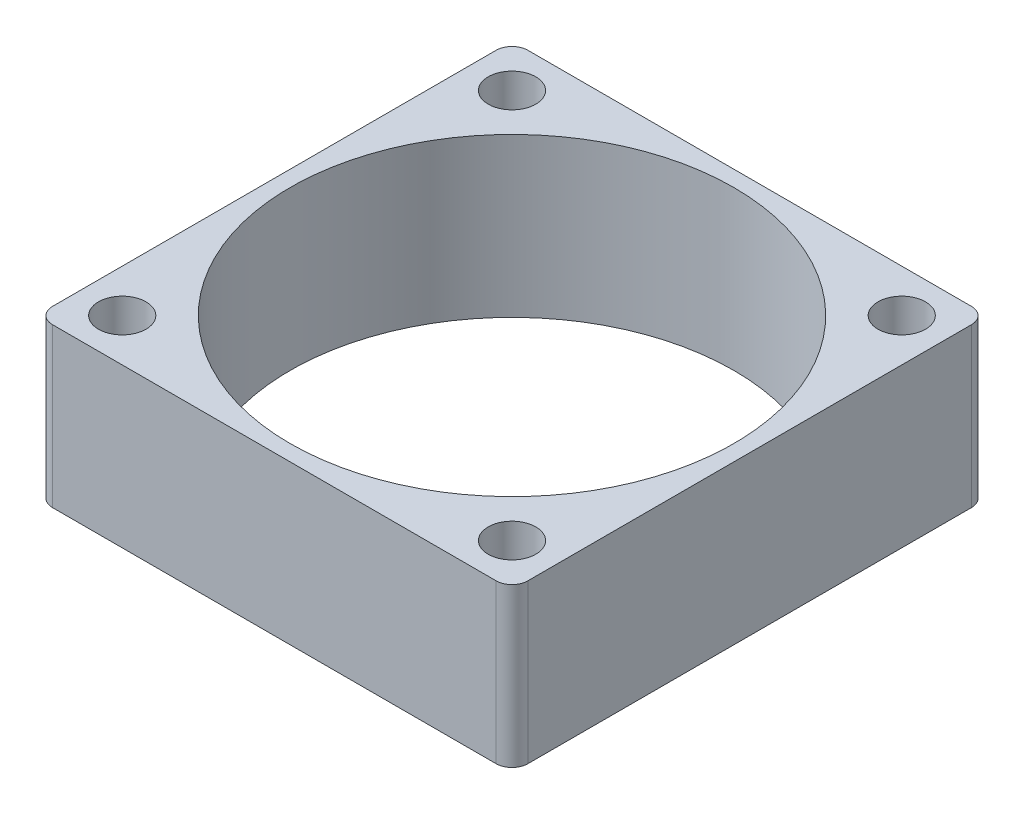
SolidWorks part; units mm, degrees
ref_plane "前视基准面" through (0, 0, 0) normal (0, 0, 1) x (1, 0, 0)
ref_plane "上视基准面" through (0, 0, 0) normal (0, 1, 0) x (1, 0, 0)
ref_plane "右视基准面" through (0, 0, 0) normal (1, 0, 0) x (0, 0, -1)
sketch "草图1" plane through (0, 0, 0) normal (0, 1, 0) x (1, 0, 0)
  line L1 (-15, 15) -> (15, 15)
  line L2 (-15, 15) -> (-15, -15)
  line L3 (-15, -15) -> (15, -15)
  line L4 (15, 15) -> (15, -15)
  line L5 (-15, 15) -> (15, -15) construction
  line L6 (-15, -15) -> (15, 15) construction
  point P0 (0, 0)
  dimension "D1" = 30
  dimension "D2" = 30
extrude "凸台-拉伸1" add sketch "草图1" along normal blind 10
sketch "草图2" plane through (0, 10, 0) normal (0, 1, 0) x (1, 0, 0)
  line L0 (15, 15) -> (-15, 15) construction
  line L1 (-15, 15) -> (-15, -15) construction
  line L2 (15, -15) -> (15, 15) construction
  line L3 (-15, -15) -> (15, -15) construction
  circle A0 centre (-12.3, 12.3) radius 1.5
  circle A1 centre (12.3, 12.3) radius 1.5
  circle A2 centre (-12.3, -12.3) radius 1.5
  circle A3 centre (12.3, -12.3) radius 1.5
  point P8 (-11.5248, 12.4484)
  point P17 (0, 0)
  point P18 (0, 0)
  point P19 (0, 0)
  point P20 (0, 0)
  dimension "D1" = 3
  dimension "D2" = 2.7
  dimension "D3" = 2.7
  dimension "D4" = 2.7
  dimension "D5" = 2.7
extrude "切除-拉伸1" cut sketch "草图2" against normal through all
fillet "圆角1" radius 1 4 edges at (-15, 5, -15) (-15, 5, 15) (15, 5, 15) (15, 5, -15)
sketch "草图3" plane through (0, 10, 0) normal (0, 1, 0) x (1, 0, 0)
  circle A0 centre (0, 0) radius 14
  dimension "D1" = 28
extrude "切除-拉伸2" cut sketch "草图3" against normal through all
